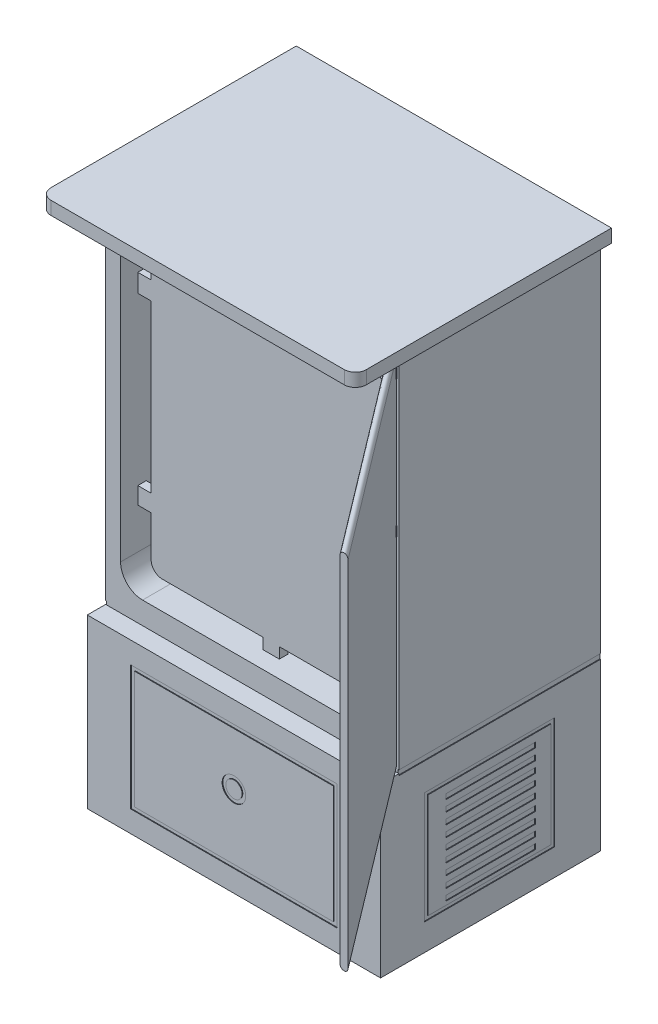
SolidWorks part; units mm, degrees
ref_plane "Alzado" through (0, 0, 0) normal (0, 0, 1) x (1, 0, 0)
ref_plane "Planta" through (0, 0, 0) normal (0, 1, 0) x (1, 0, 0)
ref_plane "Vista lateral" through (0, 0, 0) normal (1, 0, 0) x (0, 0, -1)
sketch "Croquis1" plane through (0, 0, 0) normal (0, 1, 0) x (1, 0, 0)
  line L1 (-400, 300) -> (400, 300)
  line L2 (-400, 300) -> (-400, -300)
  line L3 (-400, -300) -> (400, -300)
  line L4 (400, 300) -> (400, -300)
  line L5 (-400, 300) -> (400, -300) construction
  line L6 (-400, -300) -> (400, 300) construction
  point P0 (0, 0)
  dimension "D1" = 800
  dimension "D2" = 600
extrude "Saliente-Extruir1" add sketch "Croquis1" along normal blind 1000
sketch "Croquis2" plane through (0, 0, 300) normal (0, 0, 1) x (1, 0, 0)
  line L1 (-299.2597, 934.4838) -> (294.2721, 934.4838)
  line L2 (-359.2597, 874.4838) -> (-359.2597, 91.4597)
  line L3 (-299.2597, 31.4597) -> (294.2721, 31.4597)
  line L4 (354.2721, 874.4838) -> (354.2721, 91.4597)
  line L5 (-359.2597, 934.4838) -> (354.2721, 31.4597) construction
  line L6 (-359.2597, 31.4597) -> (354.2721, 934.4838) construction
  arc A0 (-359.2597, 91.4597) -> (-299.2597, 31.4597) centre (-299.2597, 91.4597) ccw
  arc A1 (294.2721, 31.4597) -> (354.2721, 91.4597) centre (294.2721, 91.4597) ccw
  arc A2 (294.2721, 934.4838) -> (354.2721, 874.4838) centre (294.2721, 874.4838) cw
  arc A3 (-299.2597, 934.4838) -> (-359.2597, 874.4838) centre (-299.2597, 874.4838) ccw
  point P0 (-2.4938, 482.9718)
  dimension "D1" = 60
extrude "Cortar-Extruir1" cut sketch "Croquis2" against normal blind 567
sketch "Croquis3" plane through (0, 0, 300) normal (0, 0, 1) x (1, 0, 0)
  line L0 (400, 1000) -> (400, 0) construction
  line L1 (-400, 1000) -> (400, 1000)
  line L2 (-400, 1000) -> (-400, 964.0422)
  line L3 (-400, 964.0422) -> (400, 964.0422)
  line L4 (400, 1000) -> (400, 964.0422)
extrude "Saliente-Extruir2" add sketch "Croquis3" along normal blind 99
sketch "Croquis4" plane through (400, 0, 0) normal (1, 0, 0) x (0, 0, -1)
  line L0 (300, 1000) -> (300, 0) construction
  line L1 (-399, 1000) -> (300, 1000)
  line L2 (-399, 1000) -> (-399, 964.0422)
  line L3 (-399, 964.0422) -> (300, 964.0422)
  line L4 (300, 1000) -> (300, 964.0422)
  line L5 (-399, 964.0422) -> (-399, 1000) construction
extrude "Saliente-Extruir3" add sketch "Croquis4" along normal blind 30
sketch "Croquis5" plane through (-400, 0, 0) normal (-1, 0, 0) x (0, 0, 1)
  line L0 (-300, 1000) -> (-300, 0) construction
  line L1 (399, 1000) -> (-300, 1000)
  line L2 (399, 1000) -> (399, 964.0422)
  line L3 (399, 964.0422) -> (-300, 964.0422)
  line L4 (-300, 1000) -> (-300, 964.0422)
extrude "Saliente-Extruir4" add sketch "Croquis5" along normal blind 30
fillet "Redondeo1" radius 30 2 edges at (430, 982.0211, 399) (-430, 982.0211, 399)
sketch "Croquis6" plane through (0, 0, -300) normal (0, 0, -1) x (-1, 0, 0)
  line L0 (400, 0) -> (-400, 0) construction
  line L1 (400, 0) -> (-400, 0)
  line L2 (400, 0) -> (400, -486.806)
  line L3 (400, -486.806) -> (-400, -486.806)
  line L4 (-400, 0) -> (-400, -486.806)
extrude "Saliente-Extruir5" add sketch "Croquis6" against normal up to surface (600 mm away) up to face at (-2.4938, 482.9718, 300)
sketch "Croquis8" plane through (0, 0, 300) normal (0, 0, 1) x (1, 0, 0)
  line L0 (400, 964.0422) -> (400, -486.806) construction
  line L1 (-400, 964.0422) -> (400, 964.0422)
  line L2 (-400, 964.0422) -> (-400, -29.1398)
  line L3 (-400, -29.1398) -> (400, -29.1398)
  line L4 (400, 964.0422) -> (400, -29.1398)
extrude "Cortar-Extruir3" cut sketch "Croquis8" against normal blind 50
sketch "Croquis9" plane through (-400, 0, 0) normal (-1, 0, 0) x (0, 0, 1)
  line L0 (250, 964.0422) -> (250, -29.1398) construction
  line L1 (-300, -33.9842) -> (250, -33.9842)
  line L2 (-300, -33.9842) -> (-300, -20.3179)
  line L3 (-300, -20.3179) -> (250, -20.3179)
  line L4 (250, -33.9842) -> (250, -20.3179)
  line L5 (-300, -33.9842) -> (250, -20.3179) construction
  line L6 (-300, -20.3179) -> (250, -33.9842) construction
  line L7 (-300, 964.0422) -> (-300, -486.806) construction
  point P0 (-25, -27.151)
extrude "Cortar-Extruir4" cut sketch "Croquis9" against normal blind 2
sketch "Croquis10" plane through (400, 0, 0) normal (1, 0, 0) x (0, 0, -1)
  line L0 (300, -33.9842) -> (-250, -33.9842) construction
  line L1 (300, -20.3179) -> (-250, -20.3179)
  line L2 (300, -20.3179) -> (300, -33.9842)
  line L3 (300, -33.9842) -> (-250, -33.9842)
  line L4 (-250, -20.3179) -> (-250, -33.9842)
  line L5 (300, -33.9842) -> (-250, -33.9842) construction
extrude "Cortar-Extruir5" cut sketch "Croquis10" against normal blind 2
sketch "Croquis11" plane through (-400, 0, 0) normal (-1, 0, 0) x (0, 0, 1)
  line L0 (-164.4809, -119.0564) -> (169.9361, -119.0564)
  line L1 (-174.4809, -109.0564) -> (179.9361, -109.0564)
  line L2 (-174.4809, -109.0564) -> (-174.4809, -414.4003)
  line L3 (-174.4809, -414.4003) -> (179.9361, -414.4003)
  line L4 (179.9361, -109.0564) -> (179.9361, -414.4003)
  line L5 (169.9361, -119.0564) -> (169.9361, -404.4003)
  line L6 (-164.4809, -404.4003) -> (169.9361, -404.4003)
  line L7 (-164.4809, -119.0564) -> (-164.4809, -404.4003)
  dimension "D1" = 10
extrude "Cortar-Extruir6" cut sketch "Croquis11" against normal blind 2
sketch "Croquis12" plane through (400, 0, 0) normal (1, 0, 0) x (0, 0, -1)
  line L1 (164.4809, -119.0564) -> (-169.9361, -119.0564)
  line L2 (164.4809, -119.0564) -> (164.4809, -404.4003)
  line L3 (164.4809, -404.4003) -> (-169.9361, -404.4003)
  line L4 (-169.9361, -119.0564) -> (-169.9361, -404.4003)
  line L5 (-179.9361, -414.4003) -> (174.4809, -414.4003)
  line L6 (-179.9361, -414.4003) -> (-179.9361, -109.0564)
  line L7 (-179.9361, -109.0564) -> (174.4809, -109.0564)
  line L8 (174.4809, -414.4003) -> (174.4809, -109.0564)
extrude "Cortar-Extruir7" cut sketch "Croquis12" against normal blind 2
sketch "Croquis13" plane through (-400, 0, 0) normal (-1, 0, 0) x (0, 0, 1)
  line L1 (-122.0253, -140.6239) -> (121.2843, -140.6239)
  line L2 (-122.0253, -140.6239) -> (-122.0253, -154.5635)
  line L3 (-122.0253, -154.5635) -> (121.2843, -154.5635)
  line L4 (121.2843, -140.6239) -> (121.2843, -154.5635)
extrude "Cortar-Extruir8" cut sketch "Croquis13" against normal blind 2
pattern_linear "MatrizL1" count 9 spacing 30 along (0, -1, 0) of "Cortar-Extruir8"
mirror "Simetría1" about plane through (0, 0, 0) normal (1, 0, 0) of "MatrizL1", "Cortar-Extruir8"
sketch "Croquis14" plane through (0, 0, 300) normal (0, 0, 1) x (1, 0, 0)
  line L0 (0, -29.1398) -> (0, -486.806) construction
  line L1 (-398, -29.1398) -> (398, -29.1398) construction
  line L2 (-400, -486.806) -> (400, -486.806) construction
  line L3 (0, -486.806) -> (0, -257.9729) construction
  line L4 (0, -257.9729) -> (400, -257.9729) construction
  line L5 (400, -29.1398) -> (400, -486.806) construction
  line L6 (-271.6025, -97.6737) -> (271.6025, -97.6737)
  line L7 (-281.6025, -87.6737) -> (281.6025, -87.6737)
  line L8 (-281.6025, -87.6737) -> (-281.6025, -428.2722)
  line L9 (-281.6025, -428.2722) -> (281.6025, -428.2722)
  line L10 (281.6025, -87.6737) -> (281.6025, -428.2722)
  line L11 (-281.6025, -87.6737) -> (281.6025, -428.2722) construction
  line L12 (-281.6025, -428.2722) -> (281.6025, -87.6737) construction
  line L13 (271.6025, -97.6737) -> (271.6025, -418.2722)
  line L14 (-271.6025, -418.2722) -> (271.6025, -418.2722)
  line L15 (-271.6025, -97.6737) -> (-271.6025, -418.2722)
  dimension "D1" = 10
extrude "Cortar-Extruir9" cut sketch "Croquis14" against normal blind 2
sketch "Croquis15" plane through (0, 0, 300) normal (0, 0, 1) x (1, 0, 0)
  circle A0 centre (0, -241.0783) radius 22.2098
  circle A1 centre (0, -241.0783) radius 32.2098
  dimension "D1" = 10
extrude "Cortar-Extruir10" cut sketch "Croquis15" against normal blind 2
sketch "Croquis17" plane through (0, 0, 250) normal (0, 0, 1) x (1, 0, 0)
  line L0 (381.9464, 950.0927) -> (381.9464, -15.6217) construction
  line L1 (392.8622, 950.0927) -> (392.8622, -15.6217)
  line L2 (371.0307, 950.0927) -> (371.0307, -15.6217)
  arc A0 (392.8622, 950.0927) -> (371.0307, 950.0927) centre (381.9464, 950.0927) ccw
  arc A1 (371.0307, -15.6217) -> (392.8622, -15.6217) centre (381.9464, -15.6217) ccw
  point P2 (381.9464, 467.2355)
sketch3d "Croquis3D1"
  line L0 (381.9464, 467.2355, 250) -> (793.4811, 467.3185, 793.1469)
sweep "Barrer1" add profiles "Croquis17" path "Croquis3D1"
sketch "Croquis18" plane through (0, 0, 250) normal (0, 0, 1) x (1, 0, 0)
  line L1 (360.0112, 930.9528) -> (394.7029, 930.9528)
  line L2 (360.0112, 930.9528) -> (360.0112, 900.4232)
  line L3 (360.0112, 900.4232) -> (394.7029, 900.4232)
  line L4 (394.7029, 930.9528) -> (394.7029, 900.4232)
  line L5 (360.0112, 930.9528) -> (394.7029, 900.4232) construction
  line L6 (360.0112, 900.4232) -> (394.7029, 930.9528) construction
  line L7 (346.0825, 23.5014) -> (390.5511, 23.5014)
  line L8 (346.0825, 23.5014) -> (346.0825, -10.0225)
  line L9 (346.0825, -10.0225) -> (390.5511, -10.0225)
  line L10 (390.5511, 23.5014) -> (390.5511, -10.0225)
  line L11 (346.0825, 23.5014) -> (390.5511, -10.0225) construction
  line L12 (346.0825, -10.0225) -> (390.5511, 23.5014) construction
  line L13 (394.7029, 554.1441) -> (360.0112, 554.1441)
  line L14 (394.7029, 554.1441) -> (394.7029, 527.4488)
  line L15 (394.7029, 527.4488) -> (360.0112, 527.4488)
  line L16 (360.0112, 554.1441) -> (360.0112, 527.4488)
  line L17 (394.7029, 554.1441) -> (360.0112, 527.4488) construction
  line L18 (394.7029, 527.4488) -> (360.0112, 554.1441) construction
  point P0 (377.357, 915.688)
  point P6 (368.3168, 6.7394)
  point P12 (377.357, 540.7964)
extrude "Saliente-Extruir6" add sketch "Croquis18" along normal blind 22
fillet "Redondeo2" radius 19 3 edges at (346.0825, 6.7394, 272) (360.0112, 540.7964, 272) (360.0112, 915.688, 272)
sketch "Croquis19" plane through (115.3743, 0, -87.4174) normal (-0.797, 0, 0.6039) x (0.6039, 0, 0.797)
  line L0 (495.2465, 46.9258) -> (495.2465, 884.1633)
  line L1 (515.2465, 6.9258) -> (1050.984, 6.9258)
  line L2 (485.2465, 36.9258) -> (485.2465, 894.1633)
  line L3 (515.2465, 924.1633) -> (1050.984, 924.1633)
  line L4 (1080.984, 36.9258) -> (1080.984, 894.1633)
  line L5 (485.2465, 6.9258) -> (1080.984, 924.1633) construction
  line L6 (485.2465, 924.1633) -> (1080.984, 6.9258) construction
  line L7 (525.2465, 914.1633) -> (1040.984, 914.1633)
  line L8 (1070.984, 46.9258) -> (1070.984, 884.1633)
  line L9 (525.2465, 16.9258) -> (1040.984, 16.9258)
  line L10 (485.2465, 6.9258) -> (1080.984, 6.9258) construction
  line L11 (1080.984, 6.9258) -> (1080.984, 924.1633) construction
  line L12 (1070.984, 16.9258) -> (1070.984, 914.1633) construction
  line L13 (495.2465, 16.9258) -> (1070.984, 16.9258) construction
  line L14 (495.2465, 16.9258) -> (495.2465, 914.1633) construction
  line L15 (485.2465, 6.9258) -> (485.2465, 924.1633) construction
  line L16 (485.2465, 924.1633) -> (1080.984, 924.1633) construction
  line L17 (495.2465, 914.1633) -> (1070.984, 914.1633) construction
  arc A0 (1050.984, 6.9258) -> (1080.984, 36.9258) centre (1050.984, 36.9258) ccw
  arc A1 (1070.984, 46.9258) -> (1040.984, 16.9258) centre (1040.984, 46.9258) cw
  arc A2 (495.2465, 46.9258) -> (525.2465, 16.9258) centre (525.2465, 46.9258) ccw
  arc A3 (515.2465, 6.9258) -> (485.2465, 36.9258) centre (515.2465, 36.9258) cw
  arc A4 (485.2465, 894.1633) -> (515.2465, 924.1633) centre (515.2465, 894.1633) cw
  arc A5 (495.2465, 884.1633) -> (525.2465, 914.1633) centre (525.2465, 884.1633) cw
  arc A6 (1050.984, 924.1633) -> (1080.984, 894.1633) centre (1050.984, 894.1633) cw
  arc A7 (1040.984, 914.1633) -> (1070.984, 884.1633) centre (1040.984, 884.1633) cw
  point P0 (783.1153, 465.5446)
  dimension "D2" = 30
  dimension "D1" = 10
extrude "Cortar-Extruir11" cut sketch "Croquis19" against normal blind 3
ref_plane "Plano1" through (0, 0, 180) normal (0, 0, 1) x (1, 0, 0)
sketch "Croquis20" plane through (0, 0, 180) normal (0, 0, 1) x (1, 0, 0)
  line L0 (354.2721, 874.4838) -> (354.2721, 91.4597) construction
  line L1 (-292.739, 60.8578) -> (301.9909, 60.8578)
  line L2 (-322.739, 90.8578) -> (-322.739, 866.5008)
  line L3 (-292.739, 896.5008) -> (301.9909, 896.5008)
  line L4 (331.9909, 90.8578) -> (331.9909, 866.5008)
  line L5 (-322.739, 60.8578) -> (331.9909, 896.5008) construction
  line L6 (-322.739, 896.5008) -> (331.9909, 60.8578) construction
  line L7 (309.7096, 751.0775) -> (354.2721, 751.0775)
  line L8 (309.7096, 751.0775) -> (309.7096, 704.3831)
  line L9 (309.7096, 704.3831) -> (354.2721, 704.3831)
  line L10 (354.2721, 751.0775) -> (354.2721, 704.3831)
  line L11 (309.7096, 751.0775) -> (354.2721, 704.3831) construction
  line L12 (309.7096, 704.3831) -> (354.2721, 751.0775) construction
  line L13 (-359.2597, 874.4838) -> (-359.2597, 91.4597) construction
  line L14 (309.7096, 223.0139) -> (354.2721, 223.0139)
  line L15 (309.7096, 223.0139) -> (309.7096, 187.0296)
  line L16 (309.7096, 187.0296) -> (354.2721, 187.0296)
  line L17 (354.2721, 223.0139) -> (354.2721, 187.0296)
  line L18 (309.7096, 223.0139) -> (354.2721, 187.0296) construction
  line L19 (309.7096, 187.0296) -> (354.2721, 223.0139) construction
  line L20 (-286.2183, 752.3134) -> (-359.2597, 752.3134)
  line L21 (-286.2183, 752.3134) -> (-286.2183, 702.6565)
  line L22 (-286.2183, 702.6565) -> (-359.2597, 702.6565)
  line L23 (-359.2597, 752.3134) -> (-359.2597, 702.6565)
  line L24 (-286.2183, 752.3134) -> (-359.2597, 702.6565) construction
  line L25 (-286.2183, 702.6565) -> (-359.2597, 752.3134) construction
  line L26 (-359.2597, 91.4597) -> (-359.2597, 874.4838) construction
  line L27 (-286.2183, 248.4841) -> (-359.2597, 248.4841)
  line L28 (-286.2183, 248.4841) -> (-286.2183, 202.2759)
  line L29 (-286.2183, 202.2759) -> (-359.2597, 202.2759)
  line L30 (-359.2597, 248.4841) -> (-359.2597, 202.2759)
  line L31 (-286.2183, 248.4841) -> (-359.2597, 202.2759) construction
  line L32 (-286.2183, 202.2759) -> (-359.2597, 248.4841) construction
  line L33 (294.2721, 934.4838) -> (-299.2597, 934.4838) construction
  line L34 (-24.1279, 858.5178) -> (33.3797, 858.5178)
  line L35 (-24.1279, 858.5178) -> (-24.1279, 934.4838)
  line L36 (-24.1279, 934.4838) -> (33.3797, 934.4838)
  line L37 (33.3797, 858.5178) -> (33.3797, 934.4838)
  line L38 (-24.1279, 858.5178) -> (33.3797, 934.4838) construction
  line L39 (-24.1279, 934.4838) -> (33.3797, 858.5178) construction
  line L40 (294.2721, 31.4597) -> (-299.2597, 31.4597) construction
  line L41 (-17.6173, 90.2559) -> (26.8692, 90.2559)
  line L42 (-17.6173, 90.2559) -> (-17.6173, 31.4597)
  line L43 (-17.6173, 31.4597) -> (26.8692, 31.4597)
  line L44 (26.8692, 90.2559) -> (26.8692, 31.4597)
  line L45 (-17.6173, 90.2559) -> (26.8692, 31.4597) construction
  line L46 (-17.6173, 31.4597) -> (26.8692, 90.2559) construction
  arc A0 (301.9909, 60.8578) -> (331.9909, 90.8578) centre (301.9909, 90.8578) ccw
  arc A1 (301.9909, 896.5008) -> (331.9909, 866.5008) centre (301.9909, 866.5008) cw
  arc A2 (-322.739, 866.5008) -> (-292.739, 896.5008) centre (-292.739, 866.5008) cw
  arc A3 (-292.739, 60.8578) -> (-322.739, 90.8578) centre (-292.739, 90.8578) cw
  point P0 (4.6259, 478.6793)
  point P18 (331.9909, 727.7303)
  point P24 (331.9909, 205.0218)
  point P29 (-322.739, 727.485)
  point P36 (-322.739, 225.38)
  point P44 (4.6259, 896.5008)
  point P50 (4.6259, 60.8578)
  dimension "D1" = 30
extrude "Saliente-Extruir7" add sketch "Croquis20" along normal blind 23 contours A3 L1 A0 L4 L16 L15 L14 L9 L8 L7 A1 L3 A2 L2 | L8 L9 L4 L7 | L10 L7 L4 L9 | L15 L16 L4 L14 | L17 L14 L4 L16 | L34 L37 L3 L35 | L3 L37 L36 L35 | L20 L23 L22 L2 | L22 L21 L20 L2 | L29 L28 L27 L2 | L27 L30 L29 L2 | L44 L41 L42 L1 | L44 L1 L42 L43
sketch "Croquis21" plane through (0, 0, -267) normal (0, 0, 1) x (1, 0, 0)
  line L1 (-267.7019, 362.983) -> (267.7019, 362.983)
  line L2 (-267.7019, 362.983) -> (-267.7019, 345.1478)
  line L3 (-267.7019, 345.1478) -> (267.7019, 345.1478)
  line L4 (267.7019, 362.983) -> (267.7019, 345.1478)
  line L5 (-267.7019, 362.983) -> (267.7019, 345.1478) construction
  line L6 (-267.7019, 345.1478) -> (267.7019, 362.983) construction
  point P0 (0, 354.0654)
extrude "Saliente-Extruir8" add sketch "Croquis21" along normal blind 218
